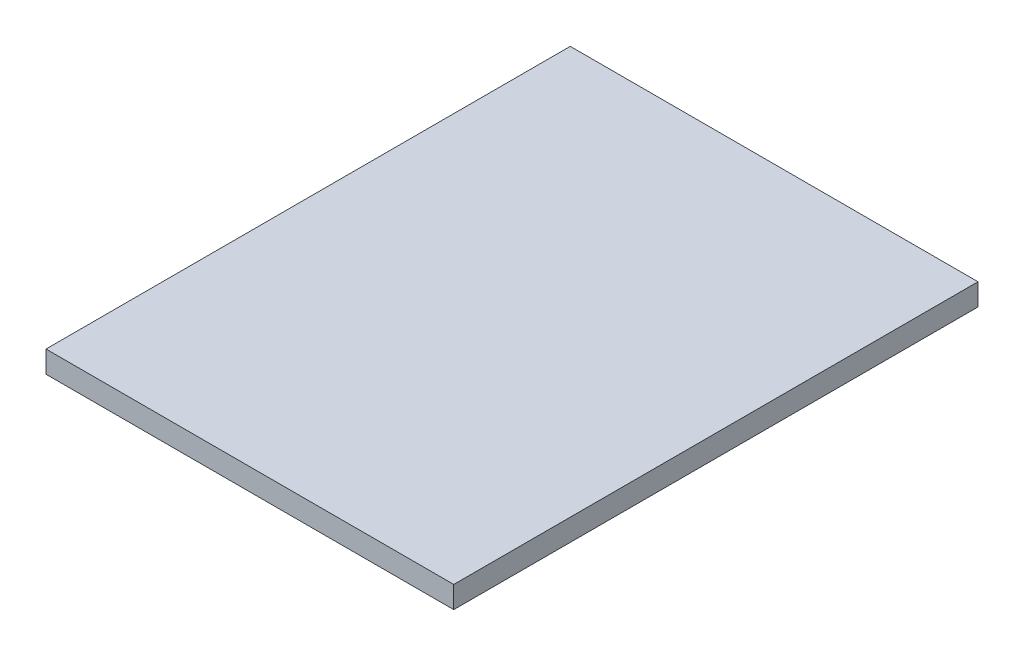
SolidWorks part; units mm, degrees
material "Acrylic (Medium-high impact)"
ref_plane "Front Plane" through (0, 0, 0) normal (0, 0, 1) x (1, 0, 0)
ref_plane "Top Plane" through (0, 0, 0) normal (0, 1, 0) x (1, 0, 0)
ref_plane "Right Plane" through (0, 0, 0) normal (1, 0, 0) x (0, 0, -1)
sketch "Sketch1" plane through (0, 0, 0) normal (0, 1, 0) x (1, 0, 0)
  line L1 (-88.9, 114.3) -> (88.9, 114.3)
  line L2 (-88.9, 114.3) -> (-88.9, -114.3)
  line L3 (-88.9, -114.3) -> (88.9, -114.3)
  line L4 (88.9, 114.3) -> (88.9, -114.3)
  line L5 (-88.9, 114.3) -> (88.9, -114.3) construction
  line L6 (-88.9, -114.3) -> (88.9, 114.3) construction
  point P0 (0, 0)
  dimension "D1" = 177.8
  dimension "D2" = 228.6
extrude "Boss-Extrude1" add sketch "Sketch1" along normal blind 9.525 contours L1 L4 L3 L2
